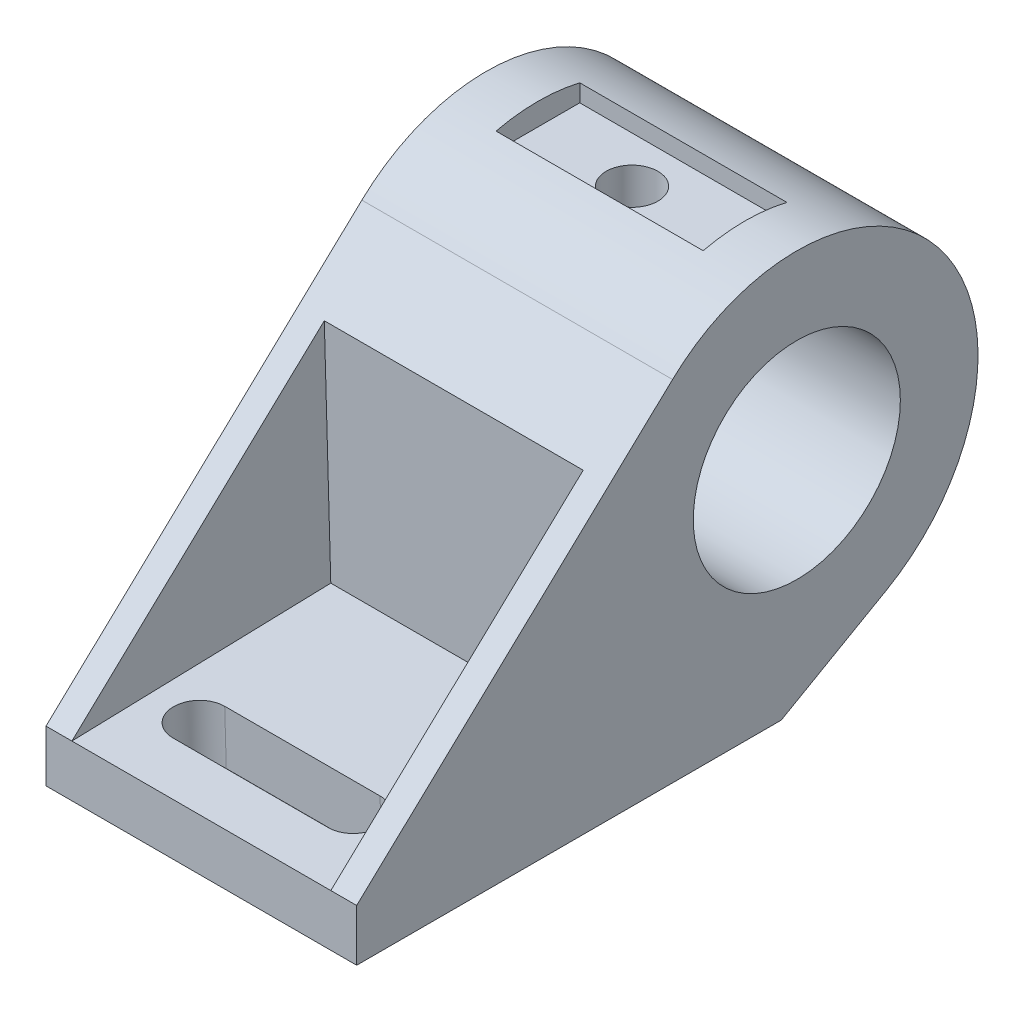
SolidWorks part; units mm, degrees
ref_plane "Front Plane" through (0, 0, 0) normal (0, 0, 1) x (1, 0, 0)
ref_plane "Top Plane" through (0, 0, 0) normal (0, 1, 0) x (1, 0, 0)
ref_plane "Right Plane" through (0, 0, 0) normal (1, 0, 0) x (0, 0, -1)
sketch "Sketch2" plane through (0, 0, 0) normal (1, 0, 0) x (0, 0, -1)
  line L0 (-79.5669, 0) -> (-79.5669, 10)
  line L1 (-79.5669, 10) -> (-18.5687, 67.4737)
  line L3 (22.7692, 11.595) -> (2.4331, 0)
  line L4 (-79.5669, 0) -> (2.4331, 0)
  arc A1 (-18.5687, 67.4737) -> (22.7692, 11.595) centre (5.4331, 42) cw
  circle A2 centre (5.4331, 42) radius 20
  dimension "D4" = 35
  dimension "D1" = 82
  dimension "D2" = 85
  dimension "D3" = 42
  dimension "D5" = 10
extrude "Boss-Extrude1" add sketch "Sketch2" against normal blind 60
move or copy body "Body-Move/Copy1" bodies to move or copy 101 copy no translate (5, 0, 0) parameters "D1"=5, "D2"=0, "D3"=0
sketch "Sketch4" plane through (0, 0, 0) normal (1, 0, 0) x (0, 0, -1)
  line L0 (-79.5669, 10) -> (-29.5669, 11.4086)
  line L1 (-29.5669, 11.4086) -> (-30.8211, 55.9293)
  line L2 (-18.5687, 67.4737) -> (-79.5669, 10) construction
  line L3 (-30.8211, 55.9293) -> (-79.5669, 10)
  dimension "D1" = 50
extrude "Cut-Extrude2" cut sketch "Sketch4" against normal blind 50
sketch "Sketch5" plane through (0, 12.2319, 0.3446) normal (0, 0.9996, 0.0282) x (1, 0, 0)
  line L0 (-40.4978, -64.2438) -> (-10.4978, -64.2438) construction
  line L1 (-40.4978, -59.2339) -> (-10.4978, -59.2339)
  line L2 (-40.4978, -69.2537) -> (-10.4978, -69.2537)
  line L3 (-50, -29.2339) -> (0, -29.2339) construction
  line L4 (-50, -79.2537) -> (0, -79.2537) construction
  arc A0 (-40.4978, -59.2339) -> (-40.4978, -69.2537) centre (-40.4978, -64.2438) ccw
  arc A1 (-10.4978, -69.2537) -> (-10.4978, -59.2339) centre (-10.4978, -64.2438) ccw
  point P2 (-25.4978, -64.2438)
  dimension "D3" = 30
  dimension "D1" = 30
  dimension "D2" = 10
extrude "Cut-Extrude3" cut sketch "Sketch5" against normal blind 50
move or copy body "Body-Move/Copy2" bodies to move or copy 105 copy no translate (5, 0, 0) parameters "D1"=5, "D2"=0, "D3"=0
sketch "Sketch12" plane through (0, 0, 0) normal (1, 0, 0) x (0, 0, -1)
  line L0 (5.4331, 77) -> (5.4331, 42) construction
  line L1 (-2.649, 72.7037) -> (13.5153, 72.7037)
  line L2 (13.5153, 72.7037) -> (13.5153, 81.885)
  line L3 (13.5153, 81.885) -> (-2.649, 81.885)
  line L4 (-2.649, 81.885) -> (-2.649, 72.7037)
  arc A0 (22.7692, 11.595) -> (-18.5687, 67.4737) centre (5.4331, 42) ccw construction
  point P8 (5.4331, 72.7037)
extrude "Cut-Extrude5" cut sketch "Sketch12" against normal blind 40
sketch "Sketch13" plane through (0, 72.7037, 0) normal (0, 1, 0) x (1, 0, 0)
  circle A0 centre (-21.0041, 4.6149) radius 5
extrude "Cut-Extrude6" cut sketch "Sketch13" against normal blind 40
